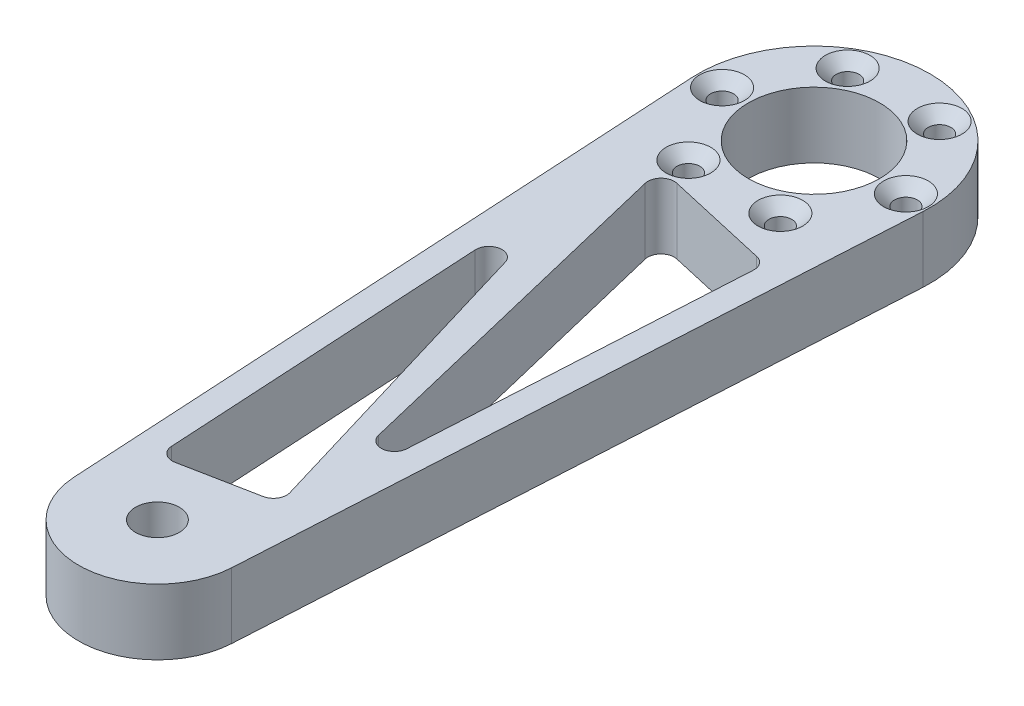
SolidWorks part; units mm, degrees
material "Thornel Mat VMA"
ref_plane "前视基准面" through (0, 0, 0) normal (0, 0, 1) x (1, 0, 0)
ref_plane "上视基准面" through (0, 0, 0) normal (0, 1, 0) x (1, 0, 0)
ref_plane "右视基准面" through (0, 0, 0) normal (1, 0, 0) x (0, 0, -1)
sketch "草图1" plane through (0, 0, 0) normal (0, 1, 0) x (1, 0, 0)
  line L0 (0, 0) -> (0, 150) construction
  line L1 (-17.9711, -1.02) -> (-26.4574, 148.4983)
  line L2 (17.9711, -1.02) -> (26.4574, 148.4983)
  line L3 (-11.9807, -0.68) -> (-20.4671, 148.8383) construction
  line L4 (11.9807, -0.68) -> (20.4671, 148.8383) construction
  line L5 (-12.741, 12.7148) -> (13.0288, 17.7851) construction
  line L6 (13.0288, 17.7851) -> (18.8303, 120) construction
  line L7 (18.8303, 120) -> (-19.3219, 128.6624) construction
  line L8 (-19.3219, 128.6624) -> (-12.741, 12.7148) construction
  line L9 (13.0288, 17.7851) -> (-19.3219, 128.6624) construction
  line L10 (14.4687, 18.2052) -> (-17.882, 129.0826) construction
  line L12 (-12.741, 12.7148) -> (-18.5544, 115.1395)
  line L13 (-18.5544, 115.1395) -> (10.7129, 17.3294)
  line L14 (10.7129, 17.3294) -> (-12.741, 12.7148)
  line L15 (13.2832, 22.2683) -> (18.8303, 120)
  line L16 (-17.882, 129.0826) -> (-17.7319, 128.5683) construction
  line L17 (18.8303, 120) -> (-12, 127)
  line L18 (-12, 127) -> (13.2832, 22.2683)
  circle A0 centre (0, 150) radius 26.5 construction
  circle A1 centre (0, 0) radius 18 construction
  circle A2 centre (0, 0) radius 5
  circle A3 centre (0, 150) radius 15
  arc A4 (-17.9711, -1.02) -> (17.9711, -1.02) centre (0, 0) ccw
  arc A5 (-26.4574, 148.4983) -> (26.4574, 148.4983) centre (0, 150) cw
  arc A6 (-20.4671, 148.8383) -> (20.4671, 148.8383) centre (0, 150) cw construction
  arc A7 (-11.9807, -0.68) -> (11.9807, -0.68) centre (0, 0) ccw construction
  dimension "D2" = 53
  dimension "D3" = 36
  dimension "D4" = 10
  dimension "D5" = 30
  dimension "D1" = 150
  dimension "D9" = 30
  dimension "D10" = 23
  dimension "D11" = 12
  dimension "D6" = 6
  dimension "D7" = 1.5
extrude "凸台-拉伸1" add sketch "草图1" along normal blind 15
fillet "圆角1" radius 3 6 edges at (18.8303, 7.5, -120) (-12, 7.5, -127) (-18.5544, 7.5, -115.1395) (-12.741, 7.5, -12.7148) (13.2832, 7.5, -22.2683) (10.7129, 7.5, -17.3294)
sketch "草图2" plane through (0, 15, 0) normal (0, 1, 0) x (1, 0, 0)
  line L0 (0, 150) -> (-21, 150) construction
  line L1 (0, 150) -> (21, 150) construction
  circle A0 centre (-21, 150) radius 2.6
  circle A1 centre (21, 150) radius 2.6
  dimension "D2" = 5.2
  dimension "D1" = 21
extrude "切除-拉伸1" cut sketch "草图2" against normal through all
pattern_circular "阵列(圆周)1" [suppressed] count 3 over 360
sketch "草图3" plane through (0, 15, 0) normal (0, 1, 0) x (1, 0, 0)
  line L0 (0, 150) -> (14.25, 150) construction
  circle A0 centre (14.25, 150) radius 2
  dimension "D2" = 4
  dimension "D1" = 14.25
extrude "切除-拉伸2" [suppressed] cut sketch "草图3" against normal through all
pattern_circular "阵列(圆周)2" [suppressed] count 3 over 360
pattern_circular "阵列(圆周)3" [suppressed] count 2 every 50
pattern_circular "阵列(圆周)4" [suppressed] count 2 every 50
pattern_circular "阵列(圆周)5" count 3 over 360 about axis through (0, 0, -150) along (0, 1, 0) of "切除-拉伸1"
chamfer "倒角1" distance 2.5 angle 45 6 edges at (-21, 15, -147.4) (-12.7517, 15, -133.1135) (12.7517, 15, -133.1135) (21, 15, -147.4) (8.2483, 15, -169.4865) (-8.2483, 15, -169.4865)
